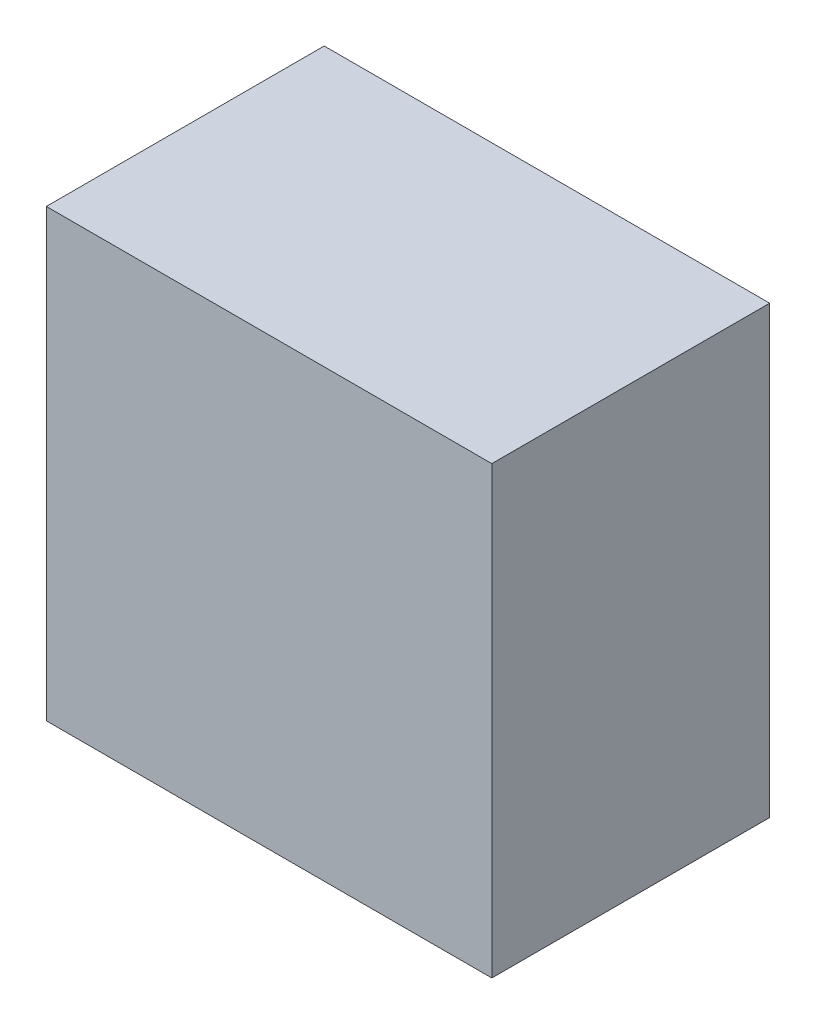
SolidWorks part; units mm, degrees
ref_plane "Front Plane" through (0, 0, 0) normal (0, 0, 1) x (1, 0, 0)
ref_plane "Top Plane" through (0, 0, 0) normal (0, 1, 0) x (1, 0, 0)
ref_plane "Right Plane" through (0, 0, 0) normal (1, 0, 0) x (0, 0, -1)
sketch "Sketch1" plane through (0, 0, 0) normal (0, 0, 1) x (1, 0, 0)
  line L0 (-0.8016, 0.8016) -> (0.8016, 0.8016)
  line L1 (0.8016, 0.8016) -> (0.8016, -0.8016)
  line L2 (0.8016, -0.8016) -> (-0.8016, -0.8016)
  line L3 (-0.8016, -0.8016) -> (-0.8016, 0.8016)
extrude "Component_Outline" add sketch "Sketch1" along normal blind 1 separate body
sketch3d "3DSketch1"
  line L0 (0, 0, 0) -> (1, 0, 0)
  line L1 (0, 0, 0) -> (0, 1, 0)
  line L2 (0, 0, 0) -> (0, 0, 1)
  point P0 (0, 0, 0)
